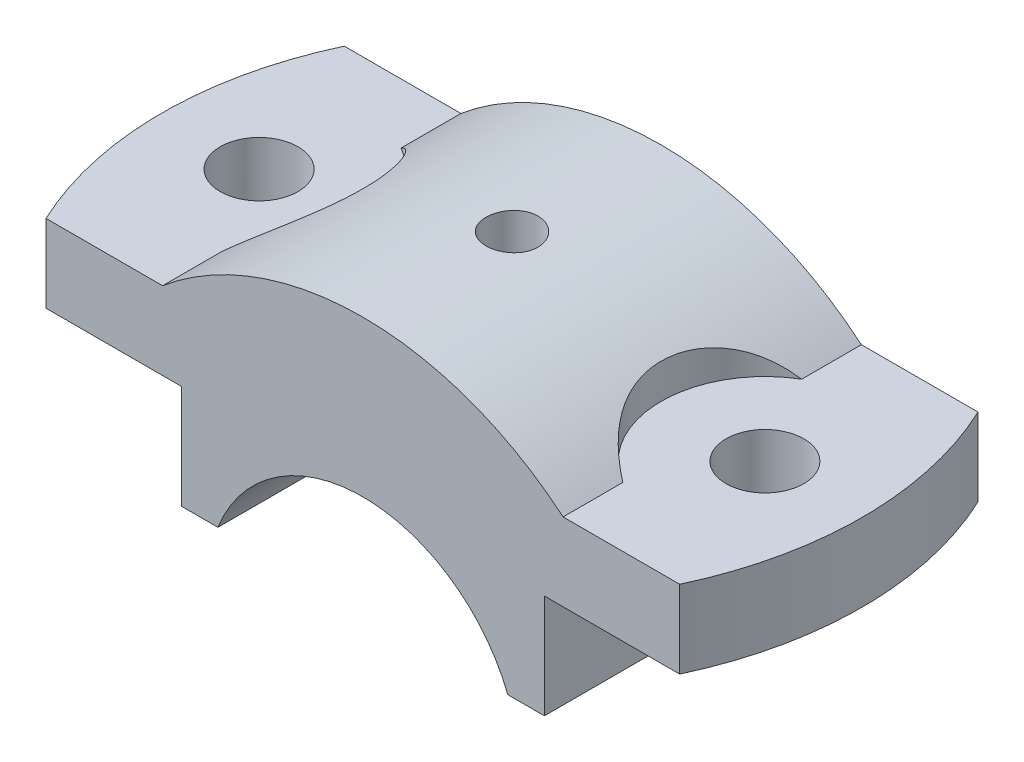
SolidWorks part; units mm, degrees
ref_plane "Front Plane" through (0, 0, 0) normal (0, 0, 1) x (1, 0, 0)
ref_plane "Top Plane" through (0, 0, 0) normal (0, 1, 0) x (1, 0, 0)
ref_plane "Right Plane" through (0, 0, 0) normal (1, 0, 0) x (0, 0, -1)
sketch "Sketch1" plane through (0, 0, 0) normal (0, 0, 1) x (1, 0, 0)
  line L0 (-59.175, 0) -> (67.875, 0) construction
  line L1 (0, 32.925) -> (0, -32.175) construction
  line L2 (-54, 3.825) -> (-30.8778, 3.825)
  line L3 (-54, 3.825) -> (-54, -8.175)
  line L4 (-54, -8.175) -> (-28, -8.175)
  line L5 (-28, -8.175) -> (-28, -24.175)
  line L6 (-28, -24.175) -> (-22.3481, -24.175)
  line L7 (28, -24.175) -> (22.3481, -24.175)
  line L8 (28, -8.175) -> (28, -24.175)
  line L9 (54, 3.825) -> (54, -8.175)
  line L10 (54, -8.175) -> (28, -8.175)
  line L11 (54, 3.825) -> (30.8778, 3.825)
  arc A0 (22.3481, -24.175) -> (-22.3481, -24.175) centre (0, -32.925) ccw
  arc A1 (30.8778, 3.825) -> (-30.8778, 3.825) centre (0, -32.925) ccw
  point P12 (0, 15.075)
  dimension "D4" = 48
  dimension "D5" = 56
  dimension "D6" = 48
  dimension "D1" = 12
  dimension "D2" = 16
  dimension "D3" = 54
  dimension "D7" = 39.25
  dimension "D8" = 24.175
extrude "Boss-Extrude1" add sketch "Sketch1" along normal mid plane 46
sketch "Sketch2" plane through (0, 3.825, 0) normal (0, 1, 0) x (1, 0, 0)
  line L0 (-48.8569, 23) -> (-68.2653, 23)
  line L1 (54, -23) -> (30.8778, -23) construction
  line L2 (54, 23) -> (30.8778, 23) construction
  line L3 (-30.8778, -23) -> (-54, -23) construction
  line L4 (-30.8778, 23) -> (-54, 23) construction
  line L6 (54, -23) -> (48.8569, -23)
  line L7 (54, 23) -> (48.8569, 23)
  line L8 (-48.8569, -23) -> (-54, -23)
  line L9 (-48.8569, 23) -> (-54, 23)
  line L10 (-68.2653, 23) -> (-68.2653, -23)
  line L11 (-68.2653, -23) -> (-54, -23)
  line L12 (54, 23) -> (85.0013, 23)
  line L13 (85.0013, 23) -> (85.0013, -23)
  line L14 (85.0013, -23) -> (54, -23)
  arc A0 (-48.8569, 23) -> (-48.8569, -23) centre (0, 0) ccw
  arc A1 (48.8569, -23) -> (48.8569, 23) centre (0, 0) ccw
  point P18 (0, 0)
  dimension "D1" = 108
extrude "Cut-Extrude1" cut sketch "Sketch2" against normal blind 46 contours A1 L6 L14 L13 L12 L7 | L0 L10 L11 L8 A0
sketch "Sketch4" plane through (0, 3.825, 0) normal (0, 1, 0) x (1, 0, 0)
  circle A0 centre (-39, 0) radius 6
  circle A1 centre (39, 0) radius 6
  point P4 (0, 0)
  dimension "D3" = 12
  dimension "D4" = 12
  dimension "D1" = 78
  dimension "D2" = 39
extrude "Cut-Extrude2" cut sketch "Sketch4" against normal blind 46
sketch "Sketch5" plane through (0, 3.825, 0) normal (0, 1, 0) x (1, 0, 0)
  line L2 (-30.8778, 13.7851) -> (-30.8778, -13.7851)
  line L3 (0, 36.847) -> (0, -44.0143) construction
  line L4 (30.8778, 13.7851) -> (30.8778, -13.7851)
  arc A0 (-30.8778, -13.7851) -> (-30.8778, 13.7851) centre (-39, 0) ccw
  arc A1 (30.8778, -13.7851) -> (30.8778, 13.7851) centre (39, 0) cw
  dimension "D1" = 32
extrude "Cut-Extrude3" cut sketch "Sketch5" along normal blind 46
ref_plane "Plane1" through (0, 15.075, 0) normal (0, 1, 0) x (1, 0, 0)
sketch "Sketch6" plane through (0, 15.075, 0) normal (0, 1, 0) x (1, 0, 0)
  circle A0 centre (0, 0) radius 4
  dimension "D1" = 8
extrude "Cut-Extrude4" cut sketch "Sketch6" against normal blind 16
sketch "Sketch7" plane through (0, 15.075, 0) normal (0, 1, 0) x (1, 0, 0)
  circle A0 centre (0, 0) radius 3
  dimension "D1" = 6
extrude "Cut-Extrude5" cut sketch "Sketch7" against normal through all
